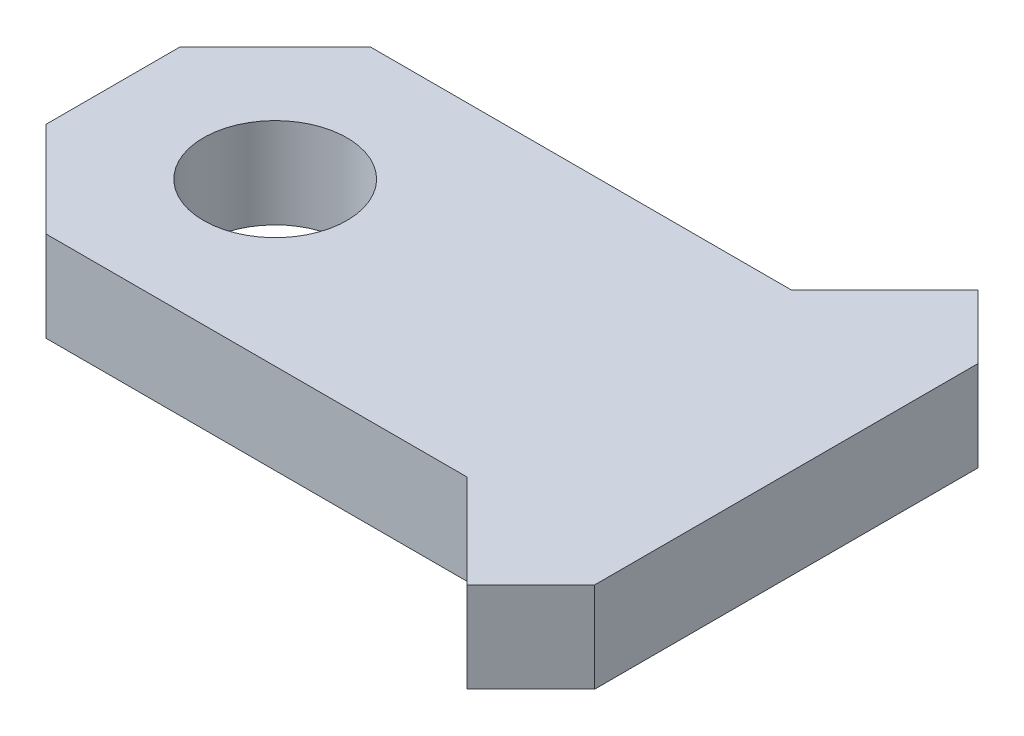
SolidWorks part; units mm, degrees
ref_plane "Front Plane" through (0, 0, 0) normal (0, 0, 1) x (1, 0, 0)
ref_plane "Top Plane" through (0, 0, 0) normal (0, 1, 0) x (1, 0, 0)
ref_plane "Right Plane" through (0, 0, 0) normal (1, 0, 0) x (0, 0, -1)
sketch "Sketch1" plane through (0, 0, 0) normal (0, 1, 0) x (1, 0, 0)
  line L0 (-7.175, 2.972) -> (-7.175, -2.972)
  line L1 (-7.175, -2.972) -> (-2.972, -7.175)
  line L2 (-2.972, -7.175) -> (15.6603, -7.175)
  line L3 (15.6603, -7.175) -> (19.799, -11.3137)
  line L4 (19.799, -11.3137) -> (22.1607, -8.952) construction
  line L5 (22.1607, -8.952) -> (22.1607, 8.952) construction
  line L6 (22.1607, 8.952) -> (19.799, 11.3137) construction
  line L7 (19.799, 11.3137) -> (15.6603, 7.175)
  line L8 (15.6603, 7.175) -> (-2.972, 7.175)
  line L9 (-2.972, 7.175) -> (-7.175, 2.972)
  line L10 (-7.175, 0) -> (-3.175, 0) construction
  line L11 (-3.175, 0) -> (0, 0) construction
  line L12 (0, 0) -> (3.175, 0) construction
  line L13 (3.175, 0) -> (0, 0) construction
  line L14 (-2.2451, -2.2451) -> (-5.0735, -5.0735) construction
  line L15 (22.1607, 8.952) -> (13.2087, 0) construction
  line L16 (13.2087, 0) -> (22.1607, -8.952) construction
  line L17 (13.2087, 0) -> (7.175, 0) construction
  line L18 (7.175, 7.175) -> (7.175, -7.175) construction
  line L19 (15.6603, 7.175) -> (8.4853, 0) construction
  line L20 (8.4853, 0) -> (15.6603, -7.175) construction
  line L21 (19.799, 11.3137) -> (15.5563, 15.5563) construction
  line L22 (15.5563, 15.5563) -> (7.175, 7.175) construction
  line L23 (3.175, 0) -> (7.175, 0) construction
  line L24 (19.799, -11.3137) -> (22.6274, -8.4853)
  line L27 (22.6274, 8.4853) -> (19.799, 11.3137)
  line L28 (22.6274, 8.4853) -> (22.6274, -8.4853)
  circle A0 centre (0, 0) radius 3.175
  point P22 (-3.175, -7.175)
  point P23 (7.175, 0)
  point P28 (22.6797, 0)
  dimension "D5" = 6.35
  dimension "D1" = 225
  dimension "D2" = 225
  dimension "D3" = 135
  dimension "D6" = 4
  dimension "D8" = 4
  dimension "D4" = 16
  dimension "D7" = 6
  dimension "D9" = 4
extrude "Boss-Extrude1" add sketch "Sketch1" along normal blind 4
equation "\"screw_diam\"= .25in"
equation "\"screw_offset\"= 4"
equation "\"screw_clearance\"= 4"
equation "\"t\" = 6"
equation "\"lip\"= 4"
equation "\"D5@Sketch1\"=\"screw_diam\""
equation "\"D6@Sketch1\"=\"screw_offset\""
equation "\"D8@Sketch1\"=\"screw_clearance\""
equation "\"w\"= 16"
equation "\"D4@Sketch1\"=\"w\""
equation "\"D7@Sketch1\"=\"t\""
equation "\"D9@Sketch1\"=\"lip\""
equation "\"h_bottom\" = 4"
equation "\"D1@Boss-Extrude1\"=\"h_bottom\""
